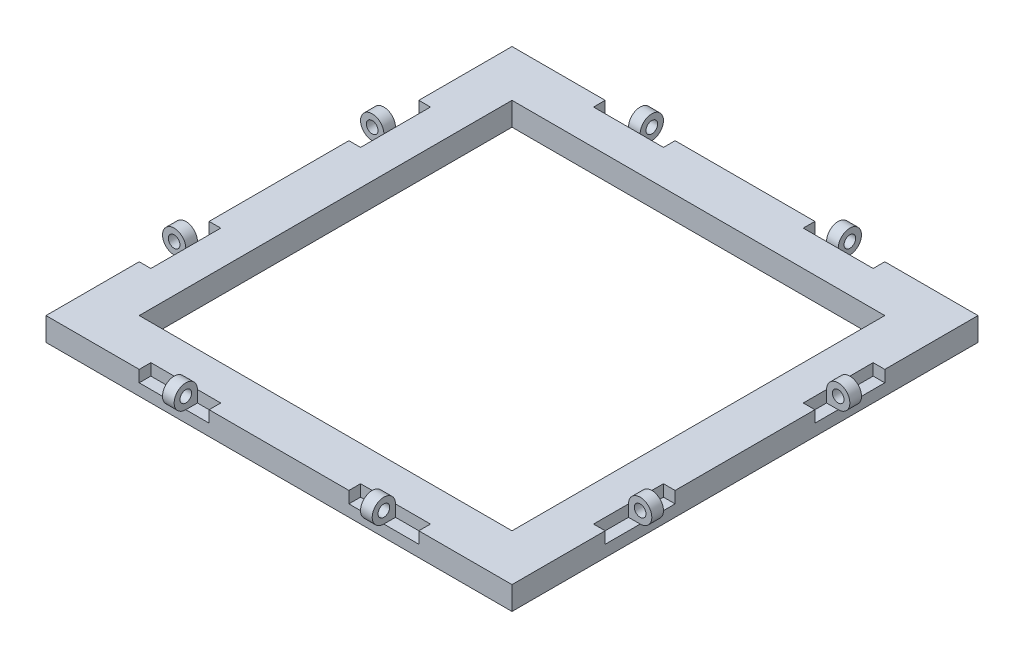
SolidWorks part; units mm, degrees
material "PET"
ref_plane "Front Plane" through (0, 0, 0) normal (0, 0, 1) x (1, 0, 0)
ref_plane "Top Plane" through (0, 0, 0) normal (0, 1, 0) x (1, 0, 0)
ref_plane "Right Plane" through (0, 0, 0) normal (1, 0, 0) x (0, 0, -1)
sketch "Sketch1" plane through (0, 0, 0) normal (0, 1, 0) x (1, 0, 0)
  line L0 (-100, 100) -> (100, 100)
  line L1 (-100, 100) -> (-100, -100)
  line L2 (100, 100) -> (100, -100)
  line L3 (-100, -100) -> (100, -100)
  circle A0 centre (0, 0) radius 0.0005
  dimension "D5" = 0.001
  dimension "D1" = 200
  dimension "D2" = 200
  dimension "D3" = 100
  dimension "D4" = 100
extrude "Boss-Extrude1" add sketch "Sketch1" along normal blind 10 contours L1 L3 L2 L0 A0
sketch "Sketch2" plane through (0, 10, 0) normal (0, 1, 0) x (1, 0, 0)
  line L0 (30, 100) -> (60, 100)
  line L1 (30, 100) -> (30, 95)
  line L2 (60, 100) -> (60, 95)
  line L3 (30, 95) -> (60, 95)
  line L5 (0, 0) -> (0, 10.1919) construction
  line L6 (-30, 95) -> (-60, 95)
  line L7 (-60, 100) -> (-60, 95)
  line L8 (-30, 100) -> (-30, 95)
  line L9 (-30, 100) -> (-60, 100)
  line L10 (-100, 100) -> (100, 100) construction
  dimension "D1" = 5
  dimension "D2" = 30
  dimension "D3" = 120
extrude "Cut-Extrude1" cut sketch "Sketch2" against normal blind 5
sketch "Sketch3" plane through (60, 0, 0) normal (-1, 0, 0) x (0, 0, 1)
  circle A0 centre (-100, 10) radius 5
  circle A1 centre (-100, 10) radius 2.5
  line M1 (-95, 10) -> (-100, 10)
  line M2 (-100, 10) -> (-100, 5)
  line M3 (-100, 5) -> (-95, 5)
  line M4 (-95, 5) -> (-95, 10)
  dimension "D1" = 5
extrude "Boss-Extrude3" add sketch "Sketch3" along normal blind 5 from offset 15 contours A1 A0 M1 M2 | A1 A0 M2 M1 | A0 M3 M4
mirror "Mirror1" about plane through (0, 0, 0) normal (1, 0, 0) of "Boss-Extrude3"
pattern_circular "CirPattern1" count 4 over 360 about axis through (0, 0, 0) along (0, 1, 0) of "Cut-Extrude1", "Boss-Extrude3", "Mirror1"
sketch "Sketch4" plane through (0, 10, 0) normal (0, 1, 0) x (1, 0, 0)
  line L0 (-100, 30) -> (-100, -30) construction
  line L1 (80, 80) -> (-80, 80)
  line L2 (80, 80) -> (80, -80)
  line L3 (80, -80) -> (-80, -80)
  line L4 (-80, 80) -> (-80, -80)
  line L5 (-100, -100) -> (-60, -100) construction
  dimension "D1" = 160
  dimension "D2" = 20
  dimension "D3" = 20
extrude "Cut-Extrude2" cut sketch "Sketch4" against normal blind 10
